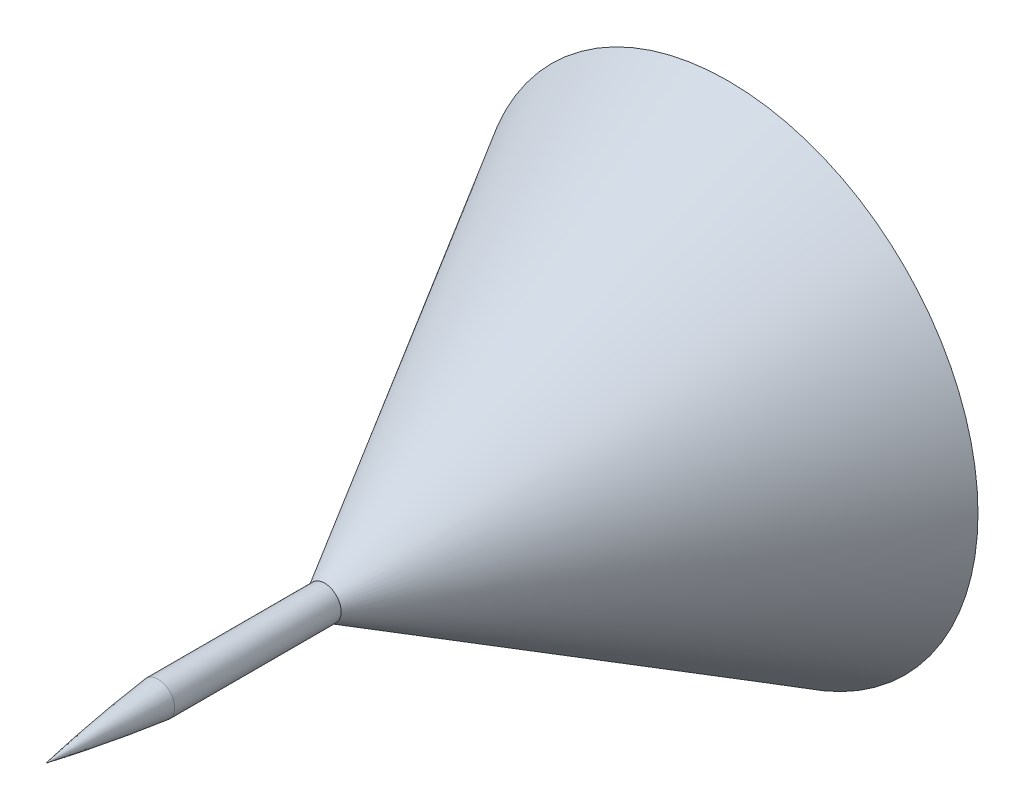
SolidWorks part; units mm, degrees
ref_plane "前基準面" through (0, 0, 0) normal (0, 0, 1) x (1, 0, 0)
ref_plane "上基準面" through (0, 0, 0) normal (0, 1, 0) x (1, 0, 0)
ref_plane "右基準面" through (0, 0, 0) normal (1, 0, 0) x (0, 0, -1)
sketch "草圖1" plane through (0, 0, 0) normal (1, 0, 0) x (0, 0, -1)
  line L0 (0, 0) -> (12.9904, 7.5)
  line L1 (0, 0) -> (2, 0)
  line L2 (0, 0) -> (75.9875, 0) construction
  line L3 (2, 0) -> (12.9904, 6.3453)
  line L4 (12.9904, 7.5) -> (12.9904, 6.3453)
  dimension "D1" = 30
  dimension "D3" = 7.5
  dimension "D5" = 1
revolve "旋轉1" add sketch "草圖1" angle 360 about L2
sketch "草圖4" plane through (0, 0, -12.9904) normal (0, 0, -1) x (-1, 0, 0)
  line L0 (0, 7.5) -> (0, -7.5) construction
  line L1 (-7.5, 0) -> (7.5, 0) construction
  circle A0 centre (0, 0) radius 7.5 construction
ref_plane "平面2" through (0, 0, 0) normal (0, 1, 0) x (1, 0, 0)
sketch "草圖5" plane through (0, 0, 0) normal (0, 1, 0) x (1, 0, 0)
  line L0 (-0.5, -4.134) -> (-0.5, 0.866)
  line L1 (-7.5, 12.9904) -> (0, 0) construction
  line L2 (0, 0) -> (0, -7.5)
  line L3 (-0.5, 0.866) -> (0, 0)
  spline S0 degree 2 poles (-0.5, -4.134) (-0.3119, -5.8267) (0, -7.5) knots 0 0 0 1 1 1
  point P8 (0, 0)
  point P9 (-0.1814, -9.035)
  point P10 (0, 0)
  point P11 (0, 0)
  point P12 (-0.1694, -6.5344)
  point P13 (0, 0)
  dimension "D1" = 7.5
  dimension "D2" = 0.5
  dimension "D3" = 5
revolve "旋轉2" add sketch "草圖5" angle 360 about L2
